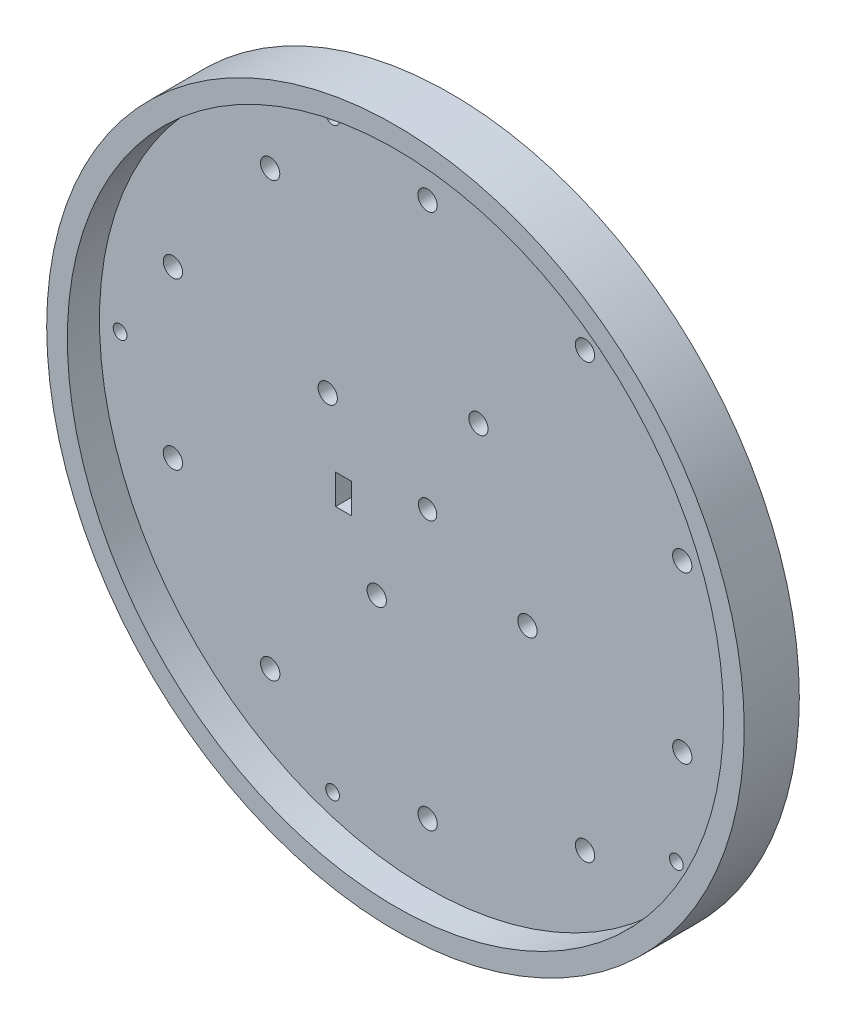
SolidWorks part; units mm, degrees
ref_plane "Front Plane" through (0, 0, 0) normal (0, 0, 1) x (1, 0, 0)
ref_plane "Top Plane" through (0, 0, 0) normal (0, 1, 0) x (1, 0, 0)
ref_plane "Right Plane" through (0, 0, 0) normal (1, 0, 0) x (0, 0, -1)
sketch "Esquisse1" plane through (0, 0, 0) normal (0, 0, 1) x (1, 0, 0)
  circle A0 centre (0, 0) radius 76
extrude "Boss.-Extru.1" add sketch "Esquisse1" along normal blind 5
sketch "Esquisse2" plane through (0, 0, 5) normal (0, 0, 1) x (1, 0, 0)
  circle A0 centre (-55.4974, 18.0212) radius 2.1
  circle A1 centre (-34.3057, 47.2) radius 2.1
  circle A2 centre (-0.0105, 58.35) radius 2.1
  circle A3 centre (34.2888, 47.2123) radius 2.1
  circle A4 centre (55.4909, 18.0411) radius 2.1
  circle A5 centre (55.4974, -18.0212) radius 2.1
  circle A6 centre (34.3057, -47.2) radius 2.1
  circle A7 centre (0.0105, -58.35) radius 2.1
  circle A8 centre (-34.2888, -47.2123) radius 2.1
  circle A9 centre (-55.4909, -18.0411) radius 2.1
  circle A10 centre (-0.0105, 58.35) radius 2.1 construction
  circle A11 centre (-11.0822, -21.7597) radius 2.1
  circle A12 centre (-11.0822, -21.7597) radius 2.1 construction
  circle A13 centre (-21.7597, 11.0822) radius 2.1
  circle A14 centre (11.0822, 21.7597) radius 2.1
  circle A15 centre (21.7597, -11.0822) radius 2.1
  point P22 (0, 0)
  point P36 (0, 0)
  dimension "D1" = 10
  dimension "D2" = 4
extrude "Enlèv. mat.-Extru.1" cut sketch "Esquisse2" against normal blind 10
sketch "Esquisse4" plane through (0, 0, 5) normal (0, 0, 1) x (1, 0, 0)
  circle A0 centre (-20.7041, -63.7208) radius 1.5
  circle A1 centre (-67, 0) radius 1.5
  circle A2 centre (-20.7041, 63.7208) radius 1.5
  circle A3 centre (54.2041, 39.3816) radius 1.5
  circle A4 centre (54.2041, -39.3816) radius 1.5
  circle A5 centre (0, 0) radius 2
  point P13 (0, 0)
  dimension "D1" = 5
  dimension "D2" = 67
extrude "Enlèv. mat.-Extru.2" cut sketch "Esquisse4" against normal blind 10
sketch "Esquisse5" plane through (0, 0, 5) normal (0, 0, 1) x (1, 0, 0)
  circle A0 centre (0, 0) radius 76
  circle A1 centre (0, 0) radius 68.5
  dimension "D1" = 137
extrude "Boss.-Extru.2" add sketch "Esquisse5" along normal blind 7
sketch "Esquisse6" plane through (0, 0, 12) normal (0, 0, 1) x (1, 0, 0)
  circle A0 centre (-20.7041, 63.7208) radius 4.5
  circle A1 centre (54.2041, 39.3816) radius 4.5
  circle A2 centre (54.2041, -39.3816) radius 4.5
  circle A3 centre (-20.7041, -63.7208) radius 4.5
  circle A4 centre (-67, 0) radius 4.5
  point P13 (0, 0)
  dimension "D1" = 5
extrude "Enlèv. mat.-Extru.3" cut sketch "Esquisse6" against normal blind 7
sketch "Esquisse7" plane through (0, 0, 12) normal (0, 0, 1) x (1, 0, 0)
  circle A0 centre (0, 0) radius 71.5
extrude "Enlèv. mat.-Extru.4" cut sketch "Esquisse7" against normal up to surface (7 mm away) up to face at (0, 0, 5)
sketch "Esquisse8" plane through (0, 0, 5) normal (0, 0, 1) x (1, 0, 0)
  line L0 (0, 0) -> (-66.9995, 0) construction
  line L1 (-20.0597, -3) -> (-16.5597, -3)
  line L2 (-20.0597, -3) -> (-20.0597, -9.5)
  line L3 (-20.0597, -9.5) -> (-16.5597, -9.5)
  line L4 (-16.5597, -3) -> (-16.5597, -9.5)
  line L10 (-21.7597, 11.0822) -> (-21.7597, -42.249) construction
  dimension "D1" = 3.5
  dimension "D2" = 6.5
  dimension "D3" = 1.7
  dimension "D4" = 3
extrude "Enlèv. mat.-Extru.5" cut sketch "Esquisse8" against normal blind 4
sketch "Esquisse10" plane through (0, 0, 0) normal (0, 0, -1) x (-1, 0, 0)
  line L0 (0, 0) -> (-66.6577, 0) construction
  circle A0 centre (-67, 0) radius 2.55
  dimension "D1" = 67
extrude "Enlèv. mat.-Extru.6" cut sketch "Esquisse10" against normal blind 4
